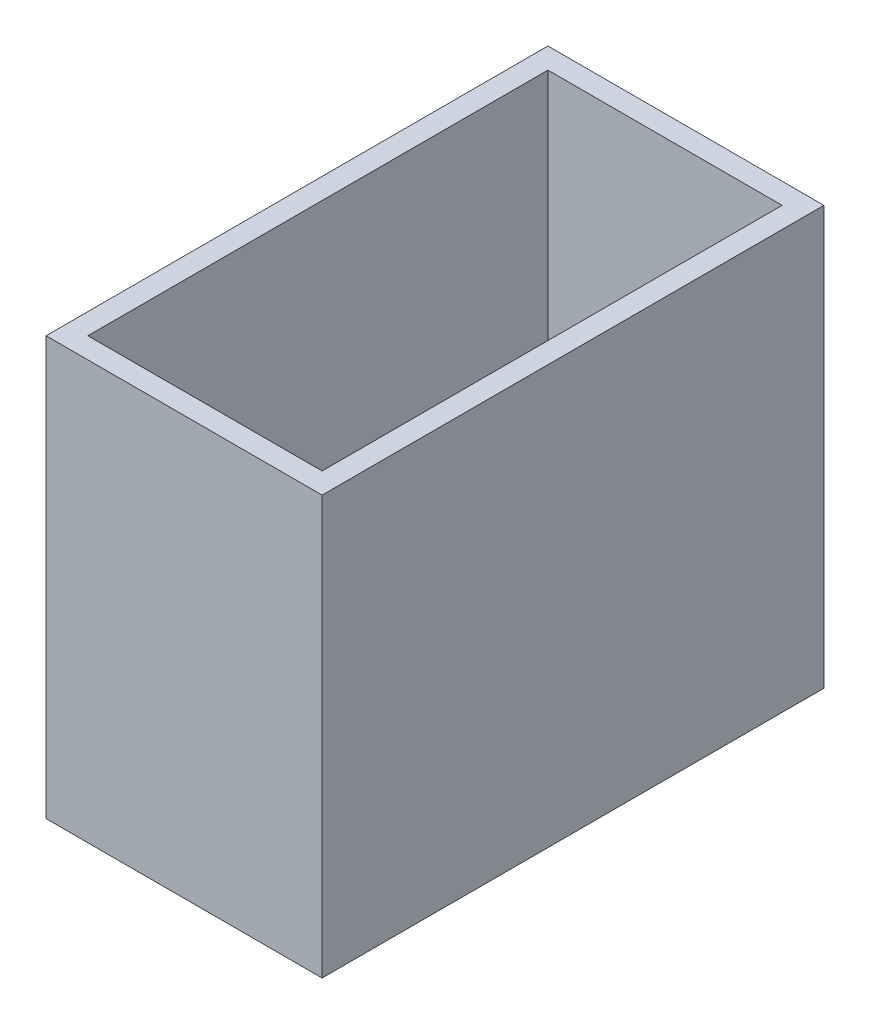
SolidWorks part; units mm, degrees
ref_plane "Front Plane" through (0, 0, 0) normal (0, 0, 1) x (1, 0, 0)
ref_plane "Top Plane" through (0, 0, 0) normal (0, 1, 0) x (1, 0, 0)
ref_plane "Right Plane" through (0, 0, 0) normal (1, 0, 0) x (0, 0, -1)
sketch "Sketch1" plane through (0, 0, 0) normal (0, 1, 0) x (1, 0, 0)
  line L0 (0, 0) -> (41.91, 0)
  line L1 (41.91, 0) -> (41.91, -76.2)
  line L2 (41.91, -76.2) -> (0, -76.2)
  line L3 (0, -76.2) -> (0, 0)
  dimension "D1" = 41.91
  dimension "D2" = 76.2
extrude "Extrude-Thin1" add sketch "Sketch1" along normal blind 63.5 thin
